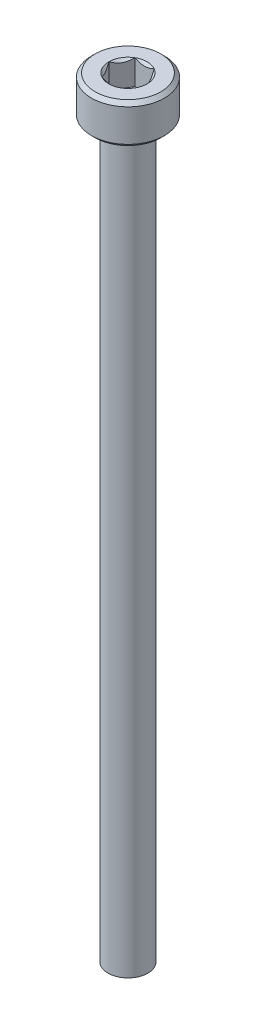
SolidWorks part; units mm, degrees
ref_plane "Front" through (0, 0, 0) normal (0, 0, 1) x (1, 0, 0)
ref_plane "Top" through (0, 0, 0) normal (0, 1, 0) x (1, 0, 0)
ref_plane "Right" through (0, 0, 0) normal (1, 0, 0) x (0, 0, -1)
sketch "Sketch1" plane through (0, 0, 0) normal (0, 1, 0) x (1, 0, 0)
  circle A0 centre (0, 0) radius 2.75
  dimension "D1" = 5.5
extrude "Boss-Extrude1" add sketch "Sketch1" along normal blind 3
sketch "Sketch2" plane through (0, 3, 0) normal (0, 1, 0) x (1, 0, 0)
  line L1 (0.7217, 1.25) -> (-0.7217, 1.25)
  line L2 (-0.7217, 1.25) -> (-1.4434, 0)
  line L3 (-1.4434, 0) -> (-0.7217, -1.25)
  line L4 (-0.7217, -1.25) -> (0.7217, -1.25)
  line L5 (0.7217, -1.25) -> (1.4434, 0)
  line L6 (1.4434, 0) -> (0.7217, 1.25)
  circle A0 centre (0, 0) radius 1.25 construction
  point P10 (0, 1.25)
  dimension "D1" = 2.5
extrude "Cut-Extrude1" cut sketch "Sketch2" against normal blind 1.88
sketch "Sketch5" plane through (0, 3, 0) normal (0, 1, 0) x (1, 0, 0)
  circle A0 centre (0, 0) radius 1.4434
extrude "Cut-Extrude2" cut sketch "Sketch5" against normal through all draft 45
chamfer "Chamfer1" distance 0.275 angle 45 2 edges at (0, 0, 2.75) (0, 3, 2.75)
sketch "草图1" plane through (0, 0, 0) normal (0, -1, 0) x (-1, 0, 0)
  circle A0 centre (0, 0) radius 1.5
  dimension "D1" = 3
extrude "凸台-拉伸1" add sketch "草图1" along normal blind 55
